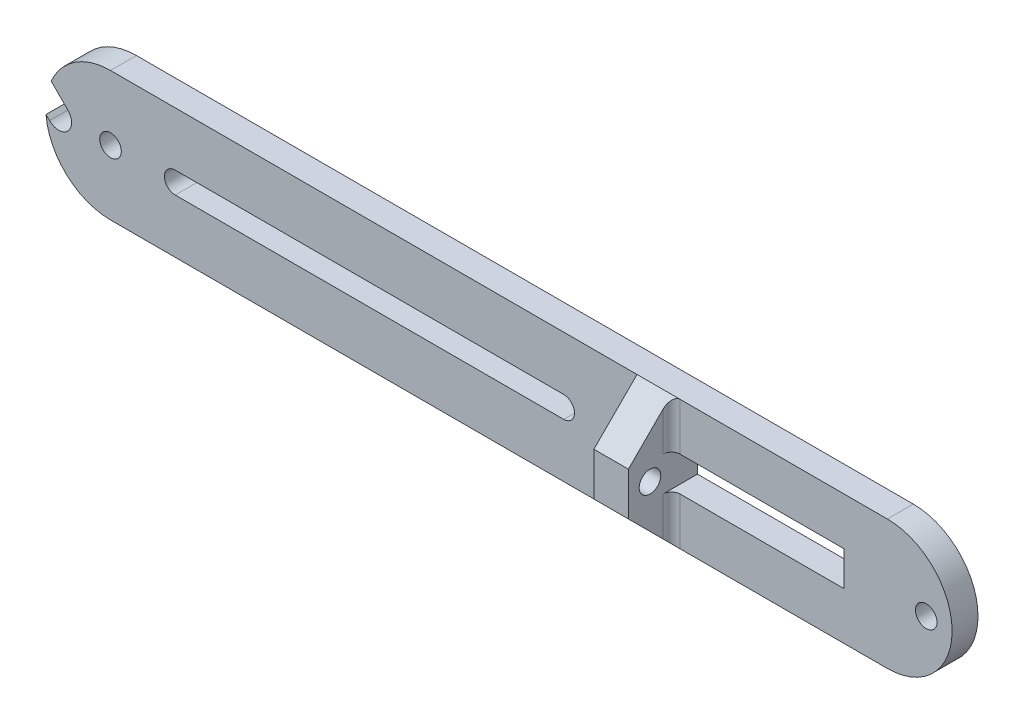
SolidWorks part; units mm, degrees
ref_plane "Plan de face" through (0, 0, 0) normal (0, 0, 1) x (1, 0, 0)
ref_plane "Plan de dessus" through (0, 0, 0) normal (0, 1, 0) x (1, 0, 0)
ref_plane "Plan de droite" through (0, 0, 0) normal (1, 0, 0) x (0, 0, -1)
sketch "Esquisse1" plane through (0, 0, 0) normal (0, 0, 1) x (1, 0, 0)
  line L0 (-74.3787, 0) -> (69.7437, 0) construction
  line L1 (0, 0) -> (0, 19.0596) construction
  line L2 (90, -15) -> (-90, -15)
  line L3 (90, 15) -> (-90, 15)
  line L4 (0, -2.5) -> (-75, -2.5)
  line L5 (40, -4) -> (80, -4)
  line L6 (40, -4) -> (40, 4)
  line L7 (40, 4) -> (80, 4)
  line L8 (80, -4) -> (80, 4)
  line L9 (40, -4) -> (80, 4) construction
  line L10 (40, 4) -> (80, -4) construction
  line L11 (0, 2.5) -> (-75, 2.5)
  line L12 (15, 0) -> (15, 2.5) construction
  line L13 (-1.729, 0) -> (-1.729, 2.5) construction
  line L14 (0, 2.5) -> (15, 2.5)
  line L15 (15, -2.5) -> (0, -2.5)
  arc A0 (90, -15) -> (90, 15) centre (90, 0) ccw
  circle A1 centre (99, 0) radius 2.5
  circle A2 centre (-90, 0) radius 2.5
  arc A3 (-90, -15) -> (-90, 15) centre (-90, 0) cw
  arc A5 (-75, 2.5) -> (-75, -2.5) centre (-75, 0) ccw
  arc A6 (15, -2.5) -> (15, 2.5) centre (15, 0) ccw
  point P4 (60, 0)
  point P17 (0, -15)
  point P20 (0, 15)
  dimension "D1" = 30
  dimension "D3" = 9
  dimension "D7" = 15
  dimension "D8" = 75
  dimension "D2" = 5
  dimension "D12" = 5
  dimension "D4" = 8
  dimension "D5" = 40
  dimension "D6" = 60
extrude "Boss.-Extru.1" add sketch "Esquisse1" along normal blind 6
sketch "Esquisse2" plane through (40, 0, 0) normal (1, 0, 0) x (0, 0, -1)
  line L0 (0, -4) -> (-6, 4) construction
  line L1 (-6, 4) -> (-6, 0) construction
  line L2 (-6, 4) -> (-6, -4) construction
  line L3 (-6, 0) -> (-15.5036, 0) construction
  line L4 (-6, 15) -> (-6, -15) construction
  line L6 (-16, 5) -> (-16, -5)
  line L8 (-6, 5) -> (-6, -5)
  line L9 (-16, 5) -> (-6, -5) construction
  line L10 (-16, -5) -> (-6, 5) construction
  line L11 (-6, -15) -> (-16, -5)
  line L12 (-6, -15) -> (-6, -5)
  line L13 (-6, 5) -> (-6, 15)
  line L14 (-6, 15) -> (-16, 5)
  circle A0 centre (-11, 0) radius 2.5
  point P7 (-11, 0)
  dimension "D3" = 5
  dimension "D1" = 10
  dimension "D2" = 10
extrude "Boss.-Extru.2" add sketch "Esquisse2" against normal blind 8
fillet "Congé2" radius 2 2 edges
sketch "Esquisse3" plane through (32, 0, 0) normal (-1, 0, 0) x (0, 0, 1)
  line L0 (11, 0) -> (11, 4) construction
  line L1 (11, 0) -> (14.4641, 2) construction
  line L2 (11, 0) -> (14.4641, -2) construction
  line L3 (11, 4) -> (14.4641, 2)
  line L4 (14.4641, 2) -> (14.4641, -2)
  line L5 (14.4641, -2) -> (11, -4)
  line L6 (7.5359, 2) -> (7.5359, -2)
  line L7 (11, 4) -> (7.5359, 2)
  line L8 (7.5359, -2) -> (11, -4)
  dimension "D2" = 60
  dimension "D3" = 60
extrude "Enlèv. mat.-Extru.1" cut sketch "Esquisse3" against normal blind 4
sketch "Esquisse4" plane through (0, 0, 6) normal (0, 0, 1) x (1, 0, 0)
  line L0 (-90, 0) -> (-105, 0) construction
  line L1 (-105, 0) -> (-102, 0) construction
  line L2 (-102, 0) -> (-104.1213, -2.1213) construction
  line L3 (-104.1213, -2.1213) -> (-99.8787, 2.1213)
  line L4 (-104.1213, -2.1213) -> (-99.8787, 2.1213)
  line L5 (-104.1213, -2.1213) -> (-108.504, 2.2614)
  line L6 (-99.8787, 2.1213) -> (-104.2614, 6.504)
  line L7 (-108.504, 2.2614) -> (-104.2614, 6.504)
  arc A0 (-90, 15) -> (-90, -15) centre (-90, 0) ccw construction
  circle A1 centre (-102, 0) radius 3
  arc M9 (-90, 15) -> (-90, -15) centre (-90, 0) ccw
  dimension "D1" = 3
  dimension "D2" = 45
extrude "Enlèv. mat.-Extru.4" cut sketch "Esquisse4" against normal blind 10 contours L3 A1 | A1 L6 M9 | A1 L5 M9 | L3 A1
